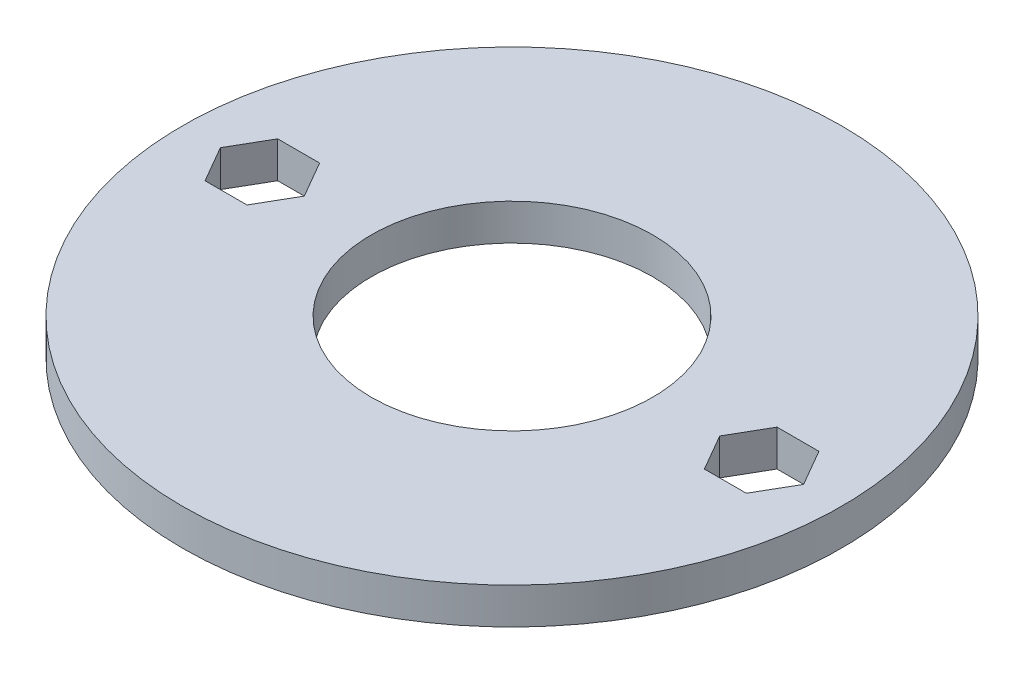
SolidWorks part; units mm, degrees
material "Balsa"
ref_plane "Front Plane" through (0, 0, 0) normal (0, 0, 1) x (1, 0, 0)
ref_plane "Top Plane" through (0, 0, 0) normal (0, 1, 0) x (1, 0, 0)
ref_plane "Right Plane" through (0, 0, 0) normal (1, 0, 0) x (0, 0, -1)
sketch "Sketch1" plane through (0, 0, 0) normal (0, 1, 0) x (1, 0, 0)
  line L0 (-36.3, 0) -> (36.3, 0) construction
  line L1 (0, 36.3) -> (0, -36.3) construction
  line L2 (25.1906, -4) -> (22.8812, 0)
  line L3 (-22.8812, 0) -> (-25.1906, 4)
  line L4 (-25.1906, 4) -> (-29.8094, 4)
  line L5 (-29.8094, 4) -> (-32.1188, 0)
  line L6 (-32.1188, 0) -> (-29.8094, -4)
  line L7 (-29.8094, -4) -> (-25.1906, -4)
  line L8 (-25.1906, -4) -> (-22.8812, 0)
  line L9 (29.8094, -4) -> (25.1906, -4)
  line L10 (32.1188, 0) -> (29.8094, -4)
  line L11 (29.8094, 4) -> (32.1188, 0)
  line L12 (25.1906, 4) -> (29.8094, 4)
  line L13 (22.8812, 0) -> (25.1906, 4)
  circle A0 centre (0, 0) radius 36.3
  circle A1 centre (27.5, 0) radius 4 construction
  circle A3 centre (0, 0) radius 15.5
  circle A4 centre (-27.5, 0) radius 4 construction
  point P25 (-27.5, 4)
  dimension "D1" = 55
  dimension "D2" = 72.6
  dimension "D3" = 8
  dimension "D4" = 31
extrude "Boss-Extrude1" add sketch "Sketch1" along normal blind 4
